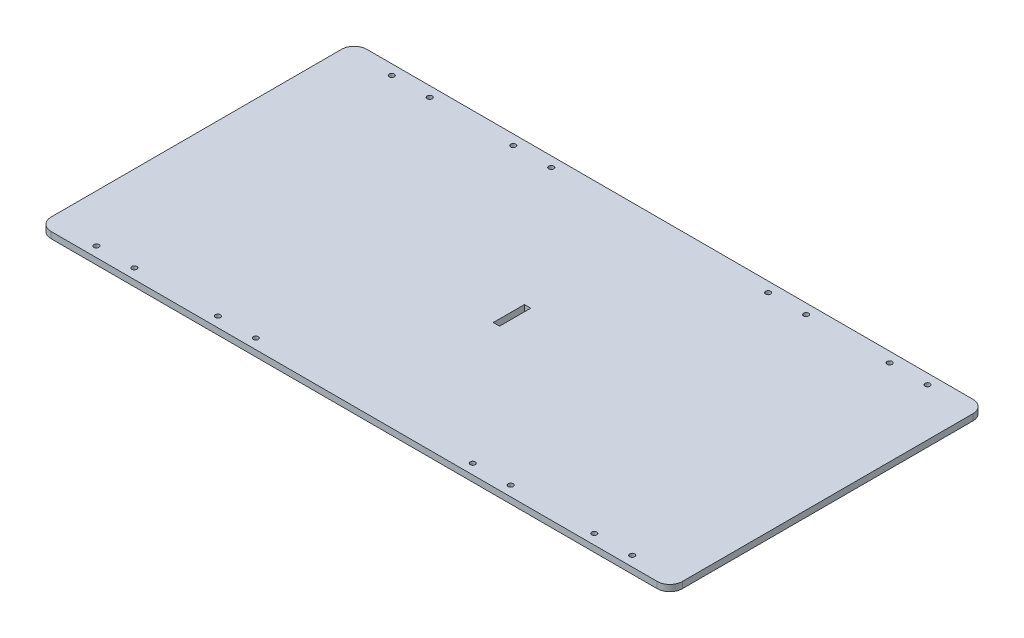
SolidWorks part; units mm, degrees
material "Medium density fiberboard, parallel to board"
ref_plane "Alzado" through (0, 0, 0) normal (0, 0, 1) x (1, 0, 0)
ref_plane "Planta" through (0, 0, 0) normal (0, 1, 0) x (1, 0, 0)
ref_plane "Vista lateral" through (0, 0, 0) normal (1, 0, 0) x (0, 0, -1)
sketch "Croquis1" plane through (0, 0, 0) normal (0, 1, 0) x (1, 0, 0)
  line L1 (240, -125) -> (-240, -125)
  line L2 (250, -115) -> (250, 115)
  line L3 (240, 125) -> (-240, 125)
  line L4 (-250, -115) -> (-250, 115)
  line L5 (250, -125) -> (-250, 125) construction
  line L6 (250, 125) -> (-250, -125) construction
  arc A0 (250, 115) -> (240, 125) centre (240, 115) ccw
  arc A1 (240, -125) -> (250, -115) centre (240, -115) ccw
  arc A2 (-240, -125) -> (-250, -115) centre (-240, -115) cw
  arc A3 (-240, 125) -> (-250, 115) centre (-240, 115) ccw
  point P0 (0, 0)
  dimension "D3" = 10
  dimension "D1" = 250
  dimension "D2" = 500
extrude "Saliente-Extruir1" add sketch "Croquis1" along normal blind 5
sketch "Croquis2" plane through (0, 5, 0) normal (0, 1, 0) x (1, 0, 0)
  line L0 (-240, -125) -> (240, -125) construction
  line L1 (-250, 115) -> (-250, -115) construction
  line L2 (0, 125) -> (0, -125) construction
  line L3 (240, 125) -> (-240, 125) construction
  line L4 (-250, 0) -> (250, 0) construction
  line L5 (250, -115) -> (250, 115) construction
  circle A0 centre (-212.2, -116.98) radius 2
  circle A1 centre (-182.15, -116.98) radius 2
  circle A2 centre (-85.9, -116.98) radius 2
  circle A3 centre (-115.95, -116.98) radius 2
  circle A4 centre (212.2, -116.98) radius 2
  circle A5 centre (182.15, -116.98) radius 2
  circle A6 centre (115.95, -116.98) radius 2
  circle A7 centre (85.9, -116.98) radius 2
  circle A8 centre (212.2, 116.98) radius 2
  circle A9 centre (182.15, 116.98) radius 2
  circle A10 centre (115.95, 116.98) radius 2
  circle A11 centre (85.9, 116.98) radius 2
  circle A12 centre (-182.15, 116.98) radius 2
  circle A13 centre (-212.2, 116.98) radius 2
  circle A14 centre (-85.9, 116.98) radius 2
  circle A15 centre (-115.95, 116.98) radius 2
  dimension "D1" = 4
  dimension "D2" = 4
  dimension "D3" = 30.05
  dimension "D4" = 8.02
  dimension "D5" = 37.8
  dimension "D6" = 8.02
  dimension "D8" = 66.2
  dimension "D9" = 85.9
  dimension "D7" = 2
extrude "Cortar-Extruir1" cut sketch "Croquis2" against normal blind 10
sketch "Croquis3" plane through (0, 5, 0) normal (0, 1, 0) x (1, 0, 0)
  line L1 (-2.5, -12.37) -> (2.5, -12.37)
  line L2 (-2.5, -12.37) -> (-2.5, 12.37)
  line L3 (-2.5, 12.37) -> (2.5, 12.37)
  line L4 (2.5, -12.37) -> (2.5, 12.37)
  line L5 (-2.5, -12.37) -> (2.5, 12.37) construction
  line L6 (-2.5, 12.37) -> (2.5, -12.37) construction
  point P0 (0, 0)
  dimension "D1" = 24.74
  dimension "D2" = 5
extrude "Cortar-Extruir2" cut sketch "Croquis3" against normal blind 10
